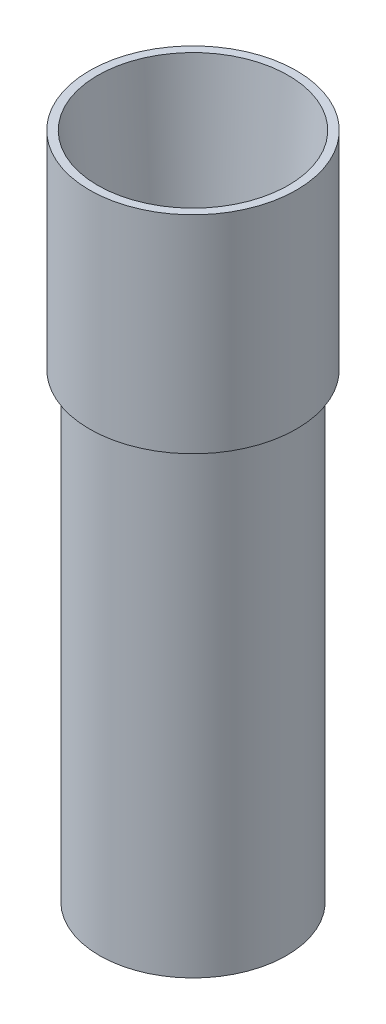
SolidWorks part; units mm, degrees
material "Brass"
ref_plane "Front Plane" through (0, 0, 0) normal (0, 0, 1) x (1, 0, 0)
ref_plane "Top Plane" through (0, 0, 0) normal (0, 1, 0) x (1, 0, 0)
ref_plane "Right Plane" through (0, 0, 0) normal (1, 0, 0) x (0, 0, -1)
sketch "Sketch1" plane through (0, 0, 0) normal (0, 1, 0) x (1, 0, 0)
  circle A0 centre (0, 0) radius 12.7
  dimension "D1" = 25.4
extrude "Boss-Extrude1" add sketch "Sketch1" against normal blind 82
sketch "Sketch2" plane through (0, 0, 0) normal (0, 1, 0) x (1, 0, 0)
  circle A0 centre (0, 0) radius 11.7
  dimension "D1" = 23.4
extrude "Cut-Extrude1" cut sketch "Sketch2" against normal blind 25.4 draft 5
sketch "Sketch3" plane through (0, -25.4, 0) normal (0, 1, 0) x (1, 0, 0)
  circle A0 centre (0, 0) radius 9.4778 construction
  circle A1 centre (0, 0) radius 9.4778
extrude "Cut-Extrude2" cut sketch "Sketch3" against normal blind 53.38
ref_plane "Plane2" through (0, -25.4068, 0) normal (0, 1, 0) x (1, 0, 0)
sketch "Sketch5" plane through (0, -25.4068, 0) normal (0, 1, 0) x (1, 0, 0)
  circle A2 centre (0, 0) radius 11.4778
  circle A3 centre (0, 0) radius 11.4778
  dimension "D1" = 2
extrude "Cut-Extrude4" cut sketch "Sketch5" against normal through all flip side to cut
sketch "Sketch4" plane through (0, -78.78, 0) normal (0, 1, 0) x (1, 0, 0)
  circle A0 centre (0, 0) radius 11.2
  dimension "D1" = 22.4
extrude "Cut-Extrude3" [suppressed] cut sketch "Sketch4" against normal through all
